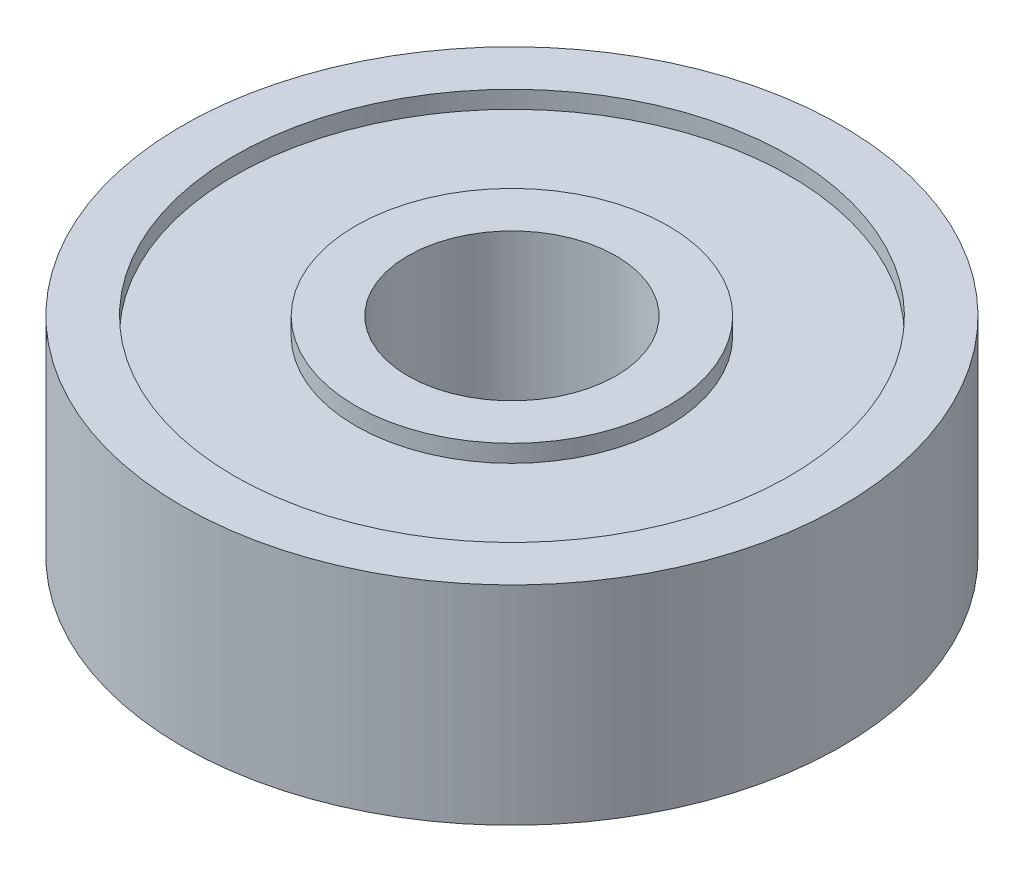
SolidWorks part; units mm, degrees
ref_plane "Plano frontal" through (0, 0, 0) normal (0, 0, 1) x (1, 0, 0)
ref_plane "Plano superior" through (0, 0, 0) normal (0, 1, 0) x (1, 0, 0)
ref_plane "Plano direito" through (0, 0, 0) normal (1, 0, 0) x (0, 0, -1)
sketch "Esboço1" plane through (0, 0, 0) normal (0, 0, 1) x (1, 0, 0)
  line L0 (0, 13.8771) -> (0, -13.8294) construction
  line L1 (3, 3) -> (4.5, 3)
  line L2 (3, 3) -> (3, -3)
  line L3 (3, -3) -> (4.5, -3)
  line L4 (4.5, 3) -> (4.5, -3)
  line L5 (8, 3) -> (9.5, 3)
  line L6 (8, 3) -> (8, -3)
  line L7 (8, -3) -> (9.5, -3)
  line L8 (9.5, 3) -> (9.5, -3)
  dimension "D1" = 9.5
  dimension "D2" = 3
  dimension "D3" = 1.5
  dimension "D4" = 1.5
  dimension "D5" = 6
  dimension "D6" = 3
revolve "Revolução1" add sketch "Esboço1" angle 360 about L0
sketch "Esboço2" plane through (0, 0, 0) normal (0, 0, 1) x (1, 0, 0)
  line L0 (8, 3) -> (-8, 3) construction
  line L1 (-8, 2.5) -> (-4.5, 2.5)
  line L2 (-8, 2.5) -> (-8, -2.5)
  line L3 (-8, -2.5) -> (-4.5, -2.5)
  line L4 (-4.5, 2.5) -> (-4.5, -2.5)
  line L5 (-8, -3) -> (8, -3) construction
  line L6 (0, 6.2682) -> (0, -6.2035) construction
  dimension "D1" = 4.5
  dimension "D2" = 8
  dimension "D3" = 0.5
  dimension "D4" = 0.5
revolve "Revolução2" add sketch "Esboço2" angle 360 about L6
